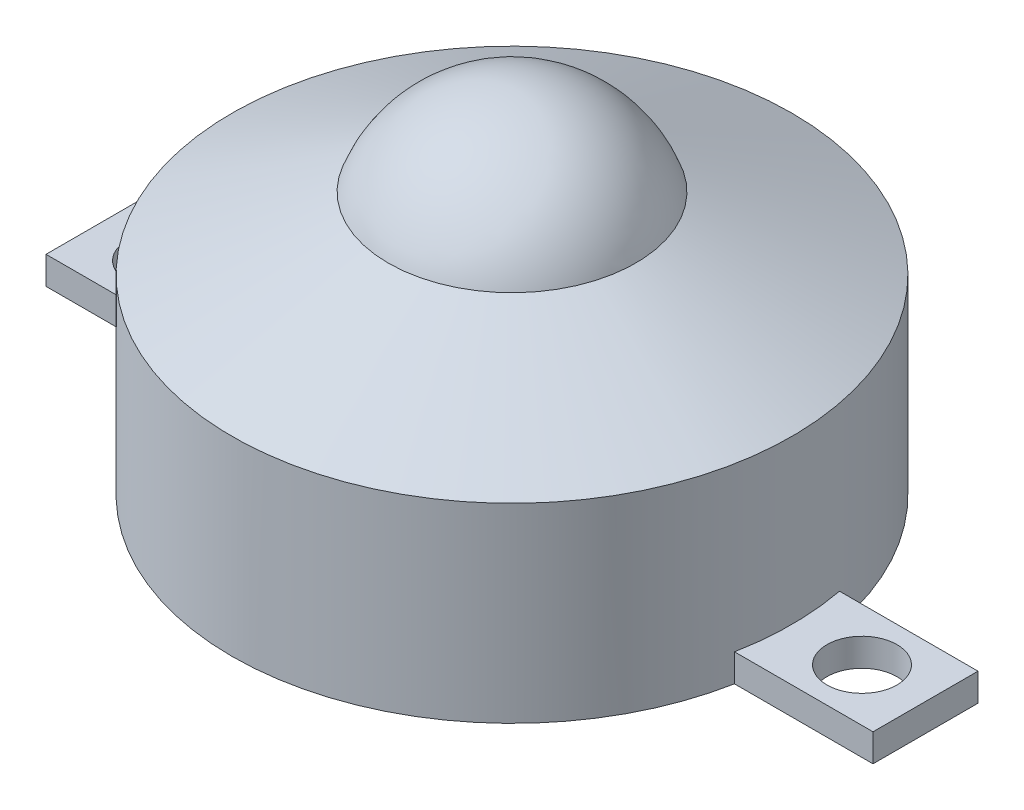
SolidWorks part; units mm, degrees
ref_plane "Front Plane" through (0, 0, 0) normal (0, 0, 1) x (1, 0, 0)
ref_plane "Top Plane" through (0, 0, 0) normal (0, 1, 0) x (1, 0, 0)
ref_plane "Right Plane" through (0, 0, 0) normal (1, 0, 0) x (0, 0, -1)
sketch "Sketch1" plane through (0, 0, 0) normal (0, 0, 1) x (1, 0, 0)
  line L1 (0, 0) -> (16, 0)
  line L2 (16, 0) -> (16, 10.8913)
  line L3 (16, 10.8913) -> (7.07, 15)
  line L4 (0, 0) -> (0, 20)
  line L5 (0, 20) -> (0, 15)
  arc A1 (0, 20) -> (7.07, 15) centre (0, 12.5015) cw
  dimension "D1" = 20
  dimension "D2" = 7.07
  dimension "D4" = 16
revolve "Revolve2" add sketch "Sketch1" angle 360 about L4
sketch "Sketch5" plane through (0, 0, 0) normal (0, -1, 0) x (1, 0, 0)
  line L5 (23.6308, 0) -> (23.6308, 3)
  line L6 (23.6308, 3) -> (15.7162, 3)
  line L7 (23.6308, 0) -> (23.6308, -3)
  line L8 (23.6308, -3) -> (15.7162, -3)
  line L9 (-23.6308, 0) -> (-23.6308, 3)
  line L10 (-23.6308, 0) -> (-23.6308, -3)
  line L11 (-23.6308, 3) -> (-15.7162, 3)
  line L12 (-23.6308, -3) -> (-15.7162, -3)
  circle A0 centre (0, 0) radius 16 construction
  circle A1 centre (-20, 0) radius 2
  circle A2 centre (20, 0) radius 2
  arc A3 (-15.7162, 3) -> (15.7162, 3) centre (0, 0) cw
  arc A4 (-15.7162, -3) -> (15.7162, -3) centre (0, 0) ccw
  dimension "D1" = 4
  dimension "D2" = 4
  dimension "D3" = 40
  dimension "D4" = 0
  dimension "D5" = 0
  dimension "D6" = 20
  dimension "D7" = 3
  dimension "D8" = 3
  dimension "D9" = 3.6308
  dimension "D10" = 3.6308
  dimension "D11" = 3
  dimension "D12" = 3
extrude "Boss-Extrude1" add sketch "Sketch5" against normal blind 1.5875
